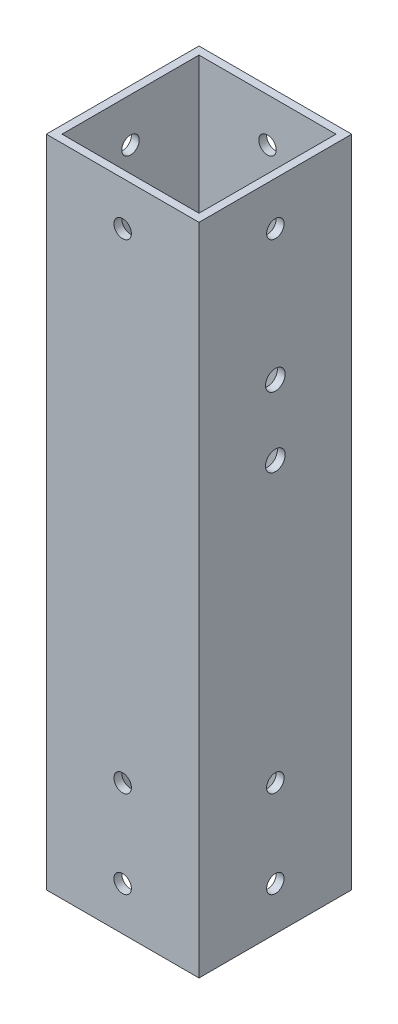
SolidWorks part; units mm, degrees
material "3003 Alloy"
ref_plane "Front Plane" through (0, 0, 0) normal (0, 0, 1) x (1, 0, 0)
ref_plane "Top Plane" through (0, 0, 0) normal (0, 1, 0) x (1, 0, 0)
ref_plane "Right Plane" through (0, 0, 0) normal (1, 0, 0) x (0, 0, -1)
sketch "Sketch1" plane through (0, 0, 0) normal (0, 1, 0) x (1, 0, 0)
  line L0 (-15.7, 0) -> (0, 0) construction
  line L1 (-15.7, 15.7) -> (15.7, 15.7)
  line L2 (-15.7, 15.7) -> (-15.7, -15.7)
  line L3 (-15.7, -15.7) -> (15.7, -15.7)
  line L4 (15.7, 15.7) -> (15.7, -15.7)
  line L5 (0, 0) -> (0, 15.7) construction
  line L6 (-17.5, 17.5) -> (17.5, 17.5)
  line L7 (17.5, 17.5) -> (17.5, -17.5)
  line L8 (-17.5, -17.5) -> (17.5, -17.5)
  line L9 (-17.5, 17.5) -> (-17.5, -17.5)
  dimension "D1" = 31.4
  dimension "D2" = 31.4
  dimension "D3" = 1.8
extrude "Boss-Extrude1" add sketch "Sketch1" along normal blind 150
sketch "Sketch3" plane through (0, 0, 17.5) normal (0, 0, 1) x (1, 0, 0)
  line L0 (17.5, 0) -> (0, 0) construction
  line L1 (0, 0) -> (0, 42.1898) construction
  circle A0 centre (0, 10) radius 2
  circle A1 centre (0, 30) radius 2
  dimension "D1" = 4
  dimension "D3" = 4
  dimension "D2" = 10
  dimension "D4" = 20
extrude "Cut-Extrude1" cut sketch "Sketch3" against normal through all
sketch "Sketch4" plane through (17.5, 0, 0) normal (1, 0, 0) x (0, 0, -1)
  line L0 (17.5, 0) -> (-17.5, 0) construction
  line L3 (0, 0) -> (0, 30) construction
  circle A0 centre (0, 10) radius 2
  circle A1 centre (0, 30) radius 2
  dimension "D1" = 4
  dimension "D2" = 4
  dimension "D3" = 10
  dimension "D4" = 20
extrude "Cut-Extrude2" cut sketch "Sketch4" against normal through all
sketch "Sketch7" plane through (17.5, 0, 0) normal (1, 0, 0) x (0, 0, -1)
  line L0 (-17.5, 140) -> (17.5, 140) construction
  line L1 (-17.5, 150) -> (-17.5, 0) construction
  line L2 (17.5, 150) -> (17.5, 0) construction
  line L3 (-17.5, 150) -> (17.5, 150) construction
  circle A0 centre (0, 140) radius 2
  dimension "D1" = 4
  dimension "D2" = 10
extrude "Cut-Extrude5" cut sketch "Sketch7" against normal blind 40
sketch "Sketch9" plane through (0, 0, 17.5) normal (0, 0, 1) x (1, 0, 0)
  line L0 (-17.5, 140) -> (17.5, 140) construction
  line L1 (-17.5, 150) -> (-17.5, 0) construction
  line L2 (17.5, 150) -> (17.5, 0) construction
  line L3 (-17.5, 150) -> (17.5, 150) construction
  circle A0 centre (0, 140) radius 2
  dimension "D1" = 4
  dimension "D2" = 10
extrude "Cut-Extrude6" cut sketch "Sketch9" against normal blind 40
sketch "Sketch11" plane through (17.5, 0, 0) normal (1, 0, 0) x (0, 0, -1)
  line L0 (0, 94) -> (0, 110) construction
  line L1 (0, 110) -> (0, 150) construction
  line L2 (-17.5, 150) -> (17.5, 150) construction
  circle A0 centre (0, 110) radius 2.25
  circle A1 centre (0, 94) radius 2.25
  dimension "D1" = 4.5
  dimension "D2" = 16
  dimension "D3" = 40
extrude "Cut-Extrude8" cut sketch "Sketch11" against normal through all
